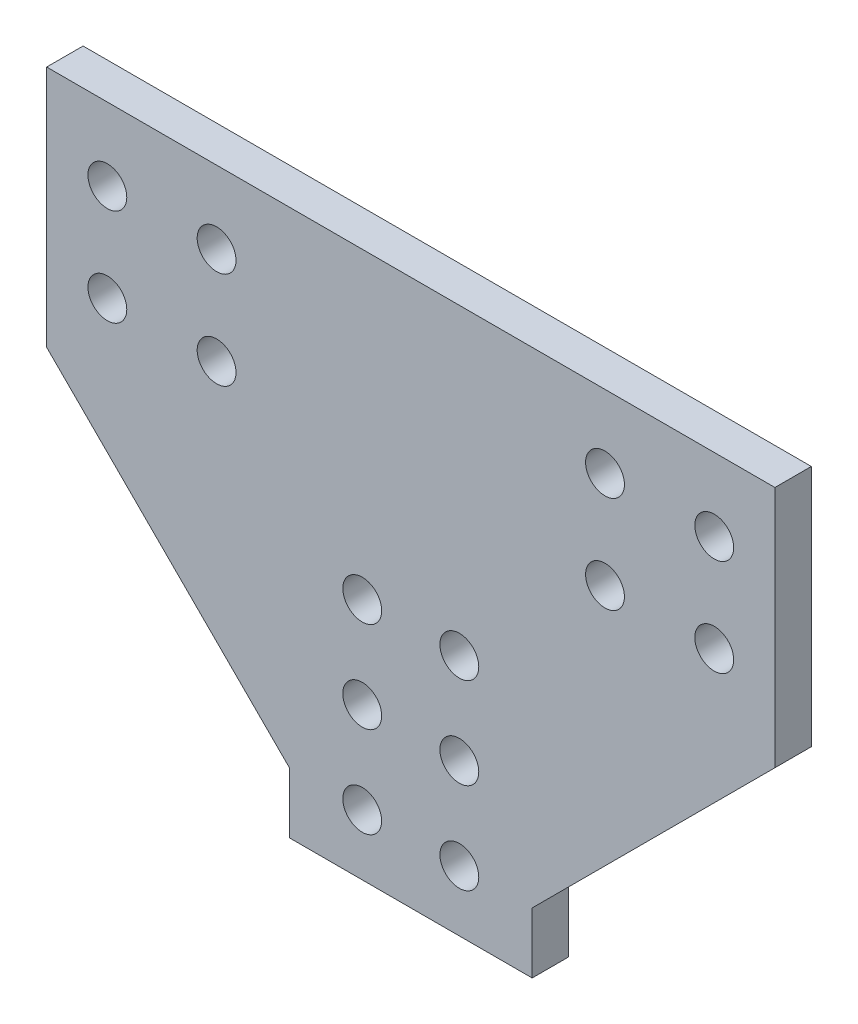
SolidWorks part; units mm, degrees
material "Thornel VCB-20 碳布"
ref_plane "前视基准面" through (0, 0, 0) normal (0, 0, 1) x (1, 0, 0)
ref_plane "上视基准面" through (0, 0, 0) normal (0, 1, 0) x (1, 0, 0)
ref_plane "右视基准面" through (0, 0, 0) normal (1, 0, 0) x (0, 0, -1)
other "Configuration Table"
sketch "草图1" plane through (0, 0, 0) normal (0, 0, 1) x (1, 0, 0)
  line L0 (0, 0) -> (0, 20)
  line L1 (0, 20) -> (60, 20)
  line L2 (60, 20) -> (60, 0)
  line L3 (60, 0) -> (40, 0) construction
  line L4 (40, 0) -> (40, -25) construction
  line L5 (40, -25) -> (20, -25)
  line L6 (20, -25) -> (20, 0) construction
  line L7 (20, 0) -> (0, 0) construction
  line L8 (60, 0) -> (40, -20)
  line L9 (40, -20) -> (40, -25)
  line L10 (0, 0) -> (20, -20)
  line L11 (20, -20) -> (20, -25)
  dimension "D1" = 20
  dimension "D2" = 20
  dimension "D3" = 25
  dimension "D4" = 20
  dimension "D5" = 45
  dimension "D6" = 45
extrude "凸台-拉伸1" add sketch "草图1" along normal blind 3
sketch "草图3" plane through (0, 0, 3) normal (0, 0, 1) x (1, 0, 0)
  line L0 (20, -25) -> (20, 20) construction
  line L1 (60, 20) -> (0, 20) construction
  line L2 (40, -25) -> (40, 20) construction
  line L3 (60, 0) -> (-0.271, 0) construction
  line L4 (20, -25) -> (40, -25) construction
  line L5 (26, -5) -> (34, -5) construction
  line L6 (26, -5) -> (26, -20) construction
  line L7 (26, -20) -> (34, -20) construction
  line L8 (34, -5) -> (34, -20) construction
  line L9 (0, 20) -> (0, 0) construction
  line L10 (5, 14) -> (55, 14) construction
  line L11 (5, 14) -> (5, 6) construction
  line L12 (5, 6) -> (55, 6) construction
  line L13 (55, 14) -> (55, 6) construction
  line L14 (60, 0) -> (60, 20) construction
  circle A0 centre (26, -5) radius 1.6
  circle A1 centre (34, -5) radius 1.6
  circle A2 centre (26, -20) radius 1.6
  circle A3 centre (34, -20) radius 1.6
  circle A4 centre (26, -12.5) radius 1.6
  circle A5 centre (34, -12.5) radius 1.6
  circle A6 centre (5, 14) radius 1.6
  circle A7 centre (5, 6) radius 1.6
  circle A8 centre (14, 14) radius 1.6
  circle A9 centre (14, 6) radius 1.6
  circle A10 centre (55, 14) radius 1.6
  circle A11 centre (55, 6) radius 1.6
  circle A12 centre (46, 14) radius 1.6
  circle A13 centre (46, 6) radius 1.6
  point P26 (34, -12.5)
  point P27 (26, -12.5)
  dimension "D5" = 3.2
  dimension "D1" = 8
  dimension "D2" = 6
  dimension "D3" = 5
  dimension "D4" = 5
  dimension "D6" = 6
  dimension "D7" = 8
  dimension "D8" = 5
  dimension "D9" = 5
  dimension "D10" = 9
  dimension "D11" = 9
  dimension "D12" = 9
  dimension "D13" = 9
extrude "切除-拉伸1" cut sketch "草图3" against normal blind 3
